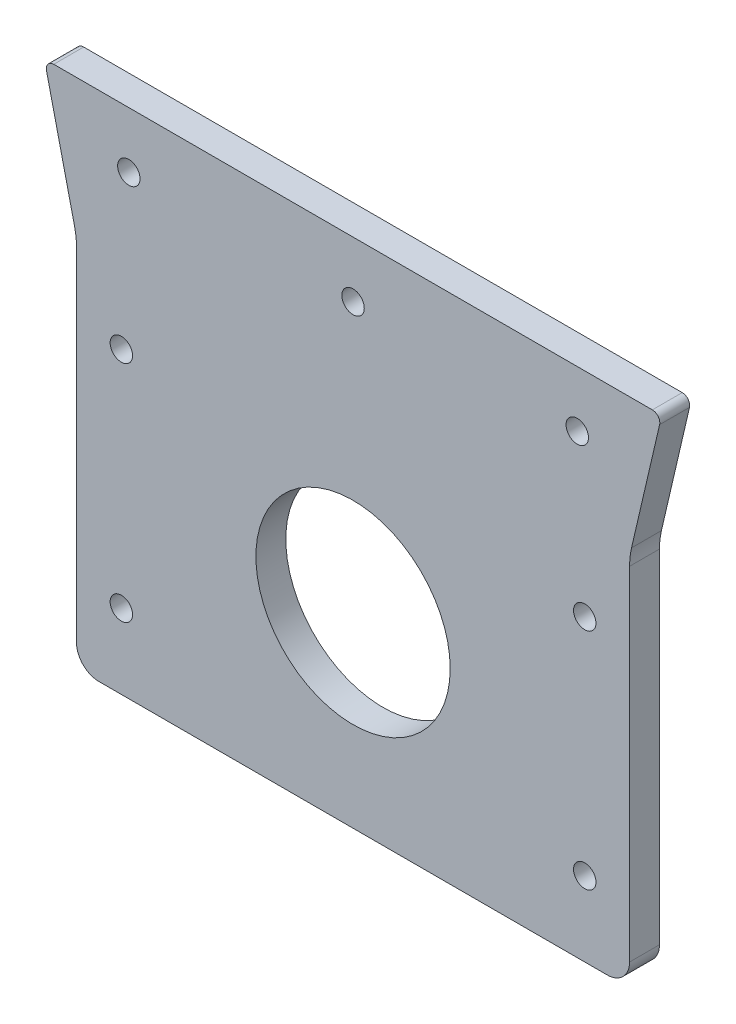
SolidWorks part; units mm, degrees
material "A-玻璃纤维"
ref_plane "前视基准面" through (0, 0, 0) normal (0, 0, 1) x (1, 0, 0)
ref_plane "上视基准面" through (0, 0, 0) normal (0, 1, 0) x (1, 0, 0)
ref_plane "右视基准面" through (0, 0, 0) normal (1, 0, 0) x (0, 0, -1)
sketch "草图1" plane through (0, 0, 0) normal (0, 0, 1) x (1, 0, 0)
  line L0 (-37, 25) -> (-42, 46.5)
  line L1 (-37, -25) -> (37, -25)
  line L2 (-37, -25) -> (-37, 25)
  line L3 (-37, 25) -> (37, 25)
  line L4 (37, -25) -> (37, 25)
  line L5 (-37, -25) -> (37, 25) construction
  line L6 (-37, 25) -> (37, -25) construction
  line L7 (37, 25) -> (42, 46.5)
  line L8 (42, 46.5) -> (-42, 46.5)
  point P0 (0, 0)
  point P8 (0, 46.5)
  dimension "D1" = 74
  dimension "D2" = 50
  dimension "D3" = 84
  dimension "D4" = 46.5
extrude "凸台-拉伸1" add sketch "草图1" along normal blind 4 contours L7 L8 L0 L3 | L1 L4 L3 L2
sketch "草图2" plane through (0, 0, 4) normal (0, 0, 1) x (1, 0, 0)
  line L1 (-31, -15) -> (31, -15)
  line L2 (-31, -15) -> (-31, 15)
  line L3 (-31, 15) -> (31, 15)
  line L4 (31, -15) -> (31, 15)
  line L5 (-31, -15) -> (31, 15) construction
  line L6 (-31, 15) -> (31, -15) construction
  circle A0 centre (31, 15) radius 1.5
  point P0 (0, 0)
  dimension "D3" = 3
  dimension "D1" = 30
  dimension "D2" = 62
extrude "切除-拉伸1" cut sketch "草图2" against normal through all contours L3 A0 L4 | L4 A0 L3
mirror "镜向1" about plane through (0, 0, 0) normal (0, 1, 0) of "切除-拉伸1"
mirror "镜向2" about plane through (0, 0, 0) normal (1, 0, 0) of "镜向1", "切除-拉伸1"
sketch "草图3" plane through (0, 0, 4) normal (0, 0, 1) x (1, 0, 0)
  circle A0 centre (0, 0) radius 13
  dimension "D1" = 26
extrude "切除-拉伸2" cut sketch "草图3" against normal through all
fillet "圆角1" radius 10 2 edges at (37, 25, 2) (-37, 25, 2)
sketch "草图4" plane through (0, 0, 4) normal (0, 0, 1) x (1, 0, 0)
  line L1 (-42, 46.5) -> (42, 46.5)
  line L2 (-42, 46.5) -> (-42, 108.5)
  line L3 (-42, 108.5) -> (42, 108.5)
  line L4 (42, 46.5) -> (42, 108.5)
  dimension "D1" = 62
extrude "凸台-拉伸2" add sketch "草图4" against normal up to surface (4 mm away) up to face at (13, 0, 0)
sketch "草图6" plane through (0, 0, 4) normal (0, 0, 1) x (1, 0, 0)
  line L0 (42, 108.5) -> (-42, 108.5) construction
  line L1 (-42, 46.5) -> (-60, 46.5)
  line L2 (-42, 46.5) -> (-42, 90.5)
  line L3 (-42, 90.5) -> (-60, 90.5)
  line L4 (-60, 46.5) -> (-60, 90.5)
  dimension "D1" = 18
  dimension "D2" = 18
extrude "凸台-拉伸3" add sketch "草图6" against normal up to surface (4 mm away) up to face at (13, 0, 0)
mirror "镜向4" about plane through (0, 0, 0) normal (1, 0, 0) of "凸台-拉伸3"
sketch "草图7" plane through (0, 0, 4) normal (0, 0, 1) x (1, 0, 0)
  line L0 (42, 90.5) -> (60, 90.5) construction
  line L1 (-32, 80.5) -> (32, 80.5)
  line L2 (-32, 80.5) -> (-32, 58.5)
  line L3 (-32, 58.5) -> (32, 58.5)
  line L4 (32, 80.5) -> (32, 58.5)
  line L5 (-32, 80.5) -> (32, 58.5) construction
  line L6 (-32, 58.5) -> (32, 80.5) construction
  line L7 (60, 46.5) -> (42, 46.5) construction
  point P0 (0, 69.5)
  dimension "D1" = 10
  dimension "D2" = 10
  dimension "D3" = 12
extrude "切除-拉伸4" cut sketch "草图7" against normal through all
sketch "草图8" plane through (0, 0, 4) normal (0, 0, 1) x (1, 0, 0)
  line L0 (0, 108.5) -> (0, 101) construction
  line L1 (-42, 108.5) -> (42, 108.5) construction
  line L2 (0, 101) -> (-24, 101) construction
  circle A0 centre (0, 101) radius 1.5
  circle A1 centre (-24, 101) radius 1.5
  dimension "D1" = 3
  dimension "D2" = 3
  dimension "D3" = 7.5
  dimension "D4" = 24
extrude "切除-拉伸5" cut sketch "草图8" against normal through all
mirror "镜向5" about plane through (0, 0, 0) normal (1, 0, 0) of "切除-拉伸5"
sketch "草图9" plane through (0, 0, 0) normal (0, 0, -1) x (-1, 0, 0)
  line L0 (-60, 68.5) -> (-52.5, 68.5) construction
  line L1 (-60, 46.5) -> (-60, 90.5) construction
  line L2 (-52.5, 68.5) -> (-52.5, 83.5) construction
  line L3 (-52.5, 68.5) -> (-52.5, 61) construction
  circle A0 centre (-52.5, 83.5) radius 1.5
  circle A1 centre (-52.5, 61) radius 1.5
  dimension "D2" = 3
  dimension "D3" = 3
  dimension "D1" = 7.5
  dimension "D4" = 7.5
  dimension "D5" = 15
extrude "切除-拉伸6" cut sketch "草图9" against normal through all
mirror "镜向6" about plane through (0, 0, 0) normal (1, 0, 0) of "切除-拉伸6"
sketch "草图10" plane through (0, 0, 0) normal (0, 0, -1) x (-1, 0, 0)
  line L0 (-42, 46.5) -> (-60, 46.5) construction
  circle A0 centre (-30, 36) radius 1.5
  dimension "D1" = 10.5
  dimension "D2" = 30
  dimension "D3" = 3
extrude "切除-拉伸7" cut sketch "草图10" against normal through all
mirror "镜向7" about plane through (0, 0, 0) normal (1, 0, 0) of "切除-拉伸7"
fillet "圆角2" radius 3 8 edges at (-32, 58.5, 2) (-32, 80.5, 2) (32, 58.5, 2) (32, 80.5, 2) (-42, 46.5, 2) (-42, 90.5, 2) (42, 46.5, 2) (42, 90.5, 2)
sketch "草图11" plane through (0, 0, 0) normal (0, 0, -1) x (-1, 0, 0)
  line L0 (42, 108.5) -> (-42, 108.5) construction
  line L1 (-60, 90.5) -> (-40, 90.5)
  line L2 (-60, 90.5) -> (-60, 108.5)
  line L3 (-60, 108.5) -> (-40, 108.5)
  line L4 (-40, 90.5) -> (-40, 108.5)
  dimension "D1" = 20
extrude "切除-拉伸8" cut sketch "草图11" against normal through all
mirror "镜向8" about plane through (0, 0, 0) normal (1, 0, 0) of "切除-拉伸8"
fillet "圆角3" radius 3 2 edges at (-40, 90.5, 2) (40, 90.5, 2)
sketch "草图12" plane through (0, 0, 0) normal (0, 0, -1) x (-1, 0, 0)
  line L0 (-60, 46.5) -> (-60, 90.5) construction
  line L1 (-60, 68.5) -> (62.8569, 68.5)
  line L2 (-60, 68.5) -> (-60, 130.0459)
  line L3 (-60, 130.0459) -> (62.8569, 130.0459)
  line L4 (62.8569, 68.5) -> (62.8569, 130.0459)
extrude "切除-拉伸9" cut sketch "草图12" against normal through all
fillet "圆角4" radius 3 2 edges at (-32, 68.5, 2) (32, 68.5, 2)
fillet "圆角5" radius 3 2 edges at (37, -25, 2) (-37, -25, 2)
sketch "草图13" plane through (0, 0, 4) normal (0, 0, 1) x (1, 0, 0)
  line L0 (-30, 36) -> (0, 36) construction
  circle A0 centre (0, 36) radius 1.5
  dimension "D2" = 3
  dimension "D1" = 30
extrude "切除-拉伸10" cut sketch "草图13" against normal through all
sketch "草图14" plane through (0, 0, 4) normal (0, 0, 1) x (1, 0, 0)
  line L1 (-85.199, 104.6267) -> (65.6069, 104.6267)
  line L2 (-85.199, 104.6267) -> (-85.199, 43.5)
  line L3 (-85.199, 43.5) -> (65.6069, 43.5)
  line L4 (65.6069, 104.6267) -> (65.6069, 43.5)
  circle A0 centre (0, 36) radius 1.5 construction
  dimension "D1" = 7.5
extrude "切除-拉伸11" cut sketch "草图14" against normal through all
fillet "圆角6" radius 1 2 edges at (41.3023, 43.5, 2) (-41.3023, 43.5, 2)
